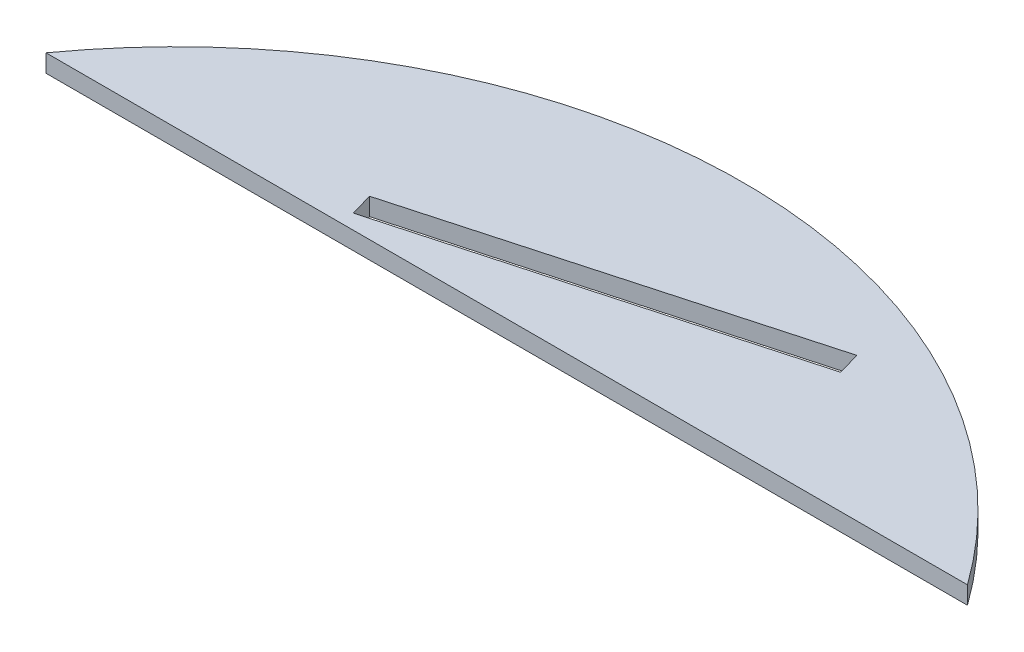
SolidWorks part; units mm, degrees
material "Balsa"
ref_plane "Front Plane" through (0, 0, 0) normal (0, 0, 1) x (1, 0, 0)
ref_plane "Top Plane" through (0, 0, 0) normal (0, 1, 0) x (1, 0, 0)
ref_plane "Right Plane" through (0, 0, 0) normal (1, 0, 0) x (0, 0, -1)
sketch "Sketch1" plane through (0, 0, 0) normal (0, 1, 0) x (1, 0, 0)
  circle A0 centre (0, 0) radius 48
  dimension "D1" = 96
extrude "Boss-Extrude1" add sketch "Sketch1" along normal blind 1.5
sketch "Sketch2" plane through (0, 1.5, 0) normal (0, 1, 0) x (1, 0, 0)
  line L0 (-38.9872, 28) -> (38.9872, 28)
  circle A0 centre (0, 0) radius 48 construction
  circle A2 centre (0, 0) radius 48
  arc A3 (-38.9872, 28) -> (38.9872, 28) centre (0, 0) ccw
  dimension "D1" = 20
  dimension "D2" = 0
extrude "Cut-Extrude1" cut sketch "Sketch2" against normal up to surface (1.5 mm away) up to face at (0, 0, 48)
sketch "Sketch3" plane through (0, 1.5, 0) normal (0, 1, 0) x (1, 0, 0)
  line L8 (17.4981, 40.1372) -> (-14.7825, 31.181)
  line L9 (18.0367, 38.2111) -> (-14.2478, 29.2538)
  line L10 (18.0367, 38.2111) -> (17.4981, 40.1372)
  line L11 (-14.2478, 29.2538) -> (-14.7825, 31.181)
  dimension "D1" = 2
  dimension "D2" = 33.5
extrude "Cut-Extrude2" cut sketch "Sketch3" against normal up to surface (1.5 mm away) up to face at (0, 0, -38)
